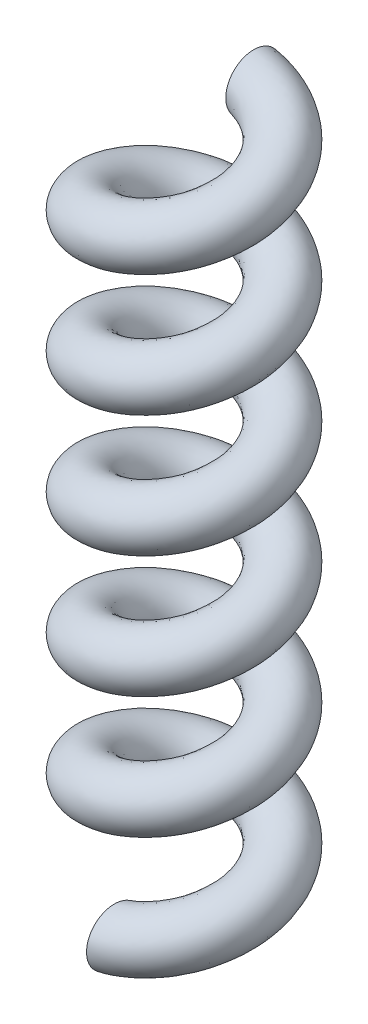
SolidWorks part; units mm, degrees
material "Alliage de zinc AC41A, brut"
ref_plane "Plan de face" through (0, 0, 0) normal (0, 0, 1) x (1, 0, 0)
ref_plane "Plan de dessus" through (0, 0, 0) normal (0, 1, 0) x (1, 0, 0)
ref_plane "Plan de droite" through (0, 0, 0) normal (1, 0, 0) x (0, 0, -1)
sketch "Esquisse5" plane through (0, 0, 0) normal (0, 1, 0) x (1, 0, 0)
  circle A0 centre (0, 0) radius 1
  dimension "D3" = 2
curve "Hélice/Spirale1" pitch 1.75 height 9.625 turns 5.5
sketch "Esquisse28" plane through (0, 0, 0) normal (1, 0, 0) x (0, 0, -1)
  line L0 (-1, 0) -> (0, 0) construction
  circle A0 centre (-1, 0) radius 0.4
  dimension "D1" = 0.8
  dimension "D2" = 1
  dimension "D3" = 1
sweep "Balayage2" add profiles "Esquisse28" path "Hélice/Spirale1"
sketch3d "3DSketch2"
  line L0 (0, 0, 0) -> (0, -0.4, 0) construction
  circle A0 centre (0, -0.4, 0) radius 1 construction
  point P3 (0, 0.6, 0)
  dimension "D2" = 2
  dimension "D1" = 0.4
